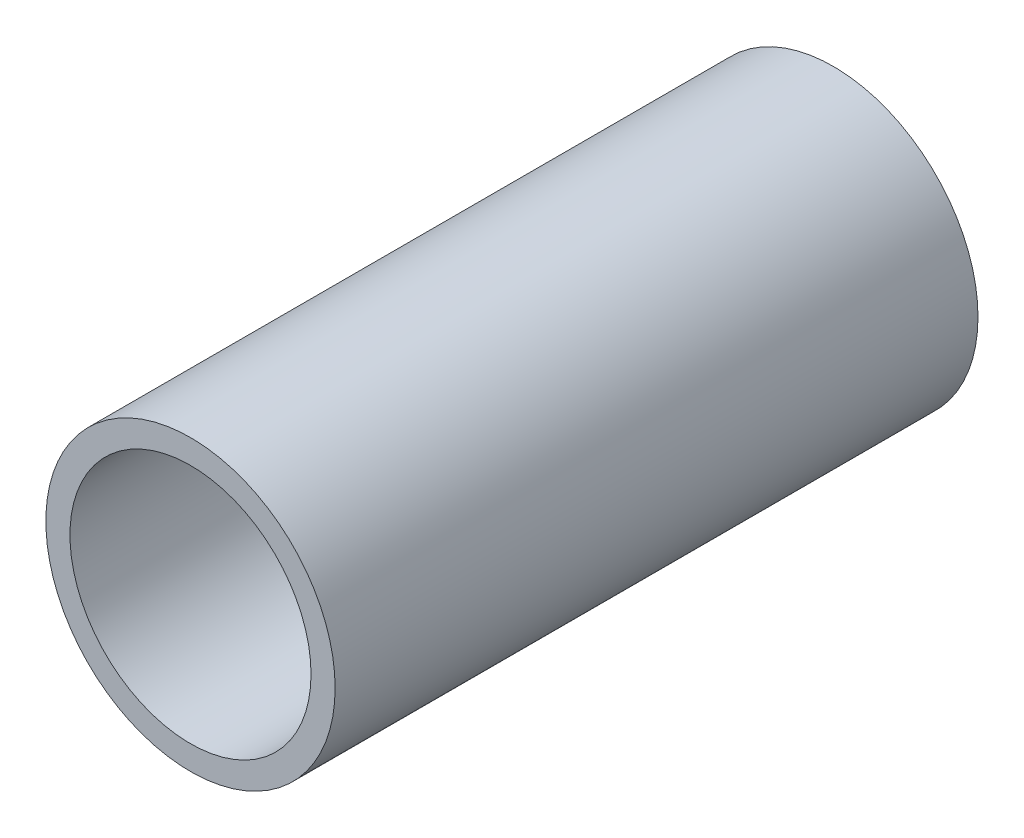
SolidWorks part; units mm, degrees
material "1345 Alloy"
ref_plane "Front Plane" through (0, 0, 0) normal (0, 0, 1) x (1, 0, 0)
ref_plane "Top Plane" through (0, 0, 0) normal (0, 1, 0) x (1, 0, 0)
ref_plane "Right Plane" through (0, 0, 0) normal (1, 0, 0) x (0, 0, -1)
sketch "Sketch1" plane through (0, 0, 0) normal (0, 0, 1) x (1, 0, 0)
  circle A0 centre (0, 0) radius 7.5
  circle A1 centre (0, 0) radius 9
extrude "Boss-Extrude1" add sketch "Sketch1" along normal blind 40
